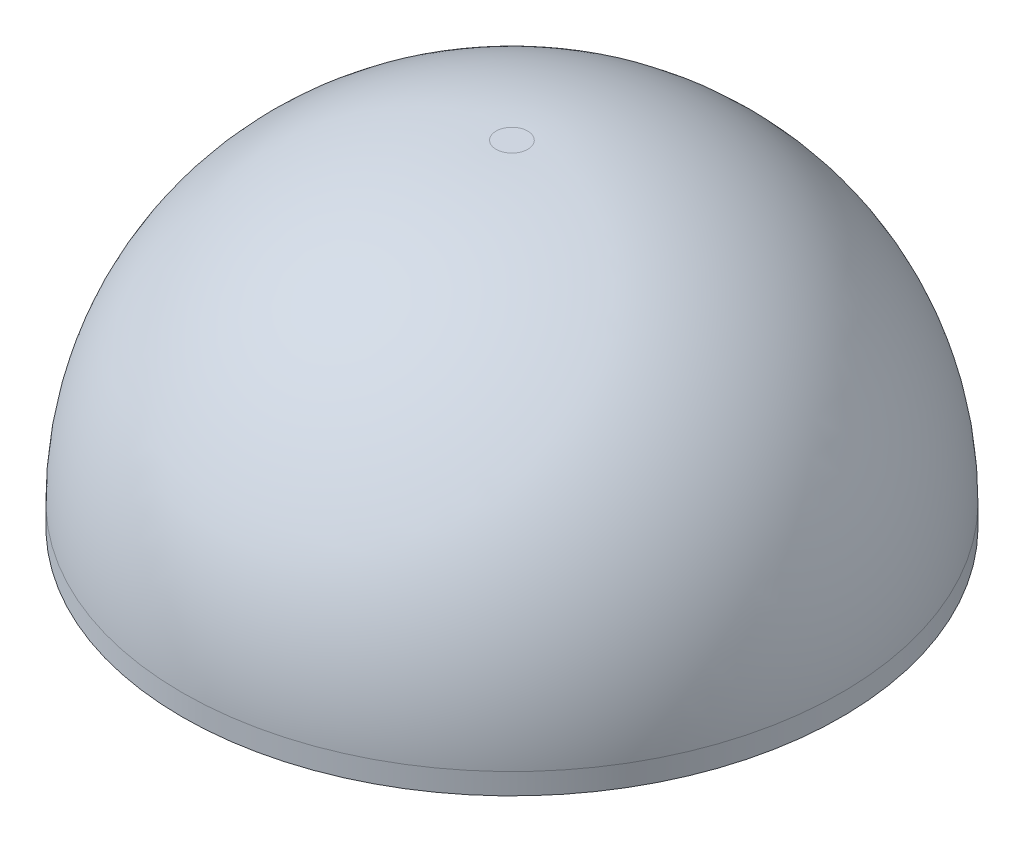
SolidWorks part; units mm, degrees
ref_plane "Front Plane" through (0, 0, 0) normal (0, 0, 1) x (1, 0, 0)
ref_plane "Top Plane" through (0, 0, 0) normal (0, 1, 0) x (1, 0, 0)
ref_plane "Right Plane" through (0, 0, 0) normal (1, 0, 0) x (0, 0, -1)
sketch "Sketch1" plane through (0, 0, 0) normal (0, 1, 0) x (1, 0, 0)
  circle A0 centre (0, 0) radius 2.5
  dimension "D1" = 5
extrude "Boss-Extrude1" add sketch "Sketch1" along normal blind 2.54
fillet "Fillet3" radius 2.38 1 edges at (0, 2.54, 2.5)
